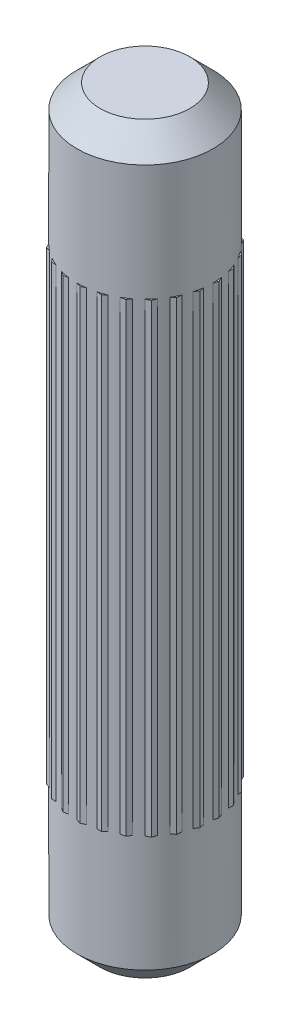
SolidWorks part; units mm, degrees
ref_plane "Front Plane" through (0, 0, 0) normal (0, 0, 1) x (1, 0, 0)
ref_plane "Top Plane" through (0, 0, 0) normal (0, 1, 0) x (1, 0, 0)
ref_plane "Right Plane" through (0, 0, 0) normal (1, 0, 0) x (0, 0, -1)
sketch "Sketch1" plane through (0, 0, 0) normal (0, 1, 0) x (1, 0, 0)
  circle A0 centre (0, 0) radius 1.465
  dimension "D1" = 2.93
extrude "Extrude1" add sketch "Sketch1" along normal mid plane 16
chamfer "Chamfer1" distance 0.5 angle 45 2 edges at (0, 8, 1.465) (0, -8, 1.465)
sketch "Sketch2" plane through (0, 0, 0) normal (0, 1, 0) x (1, 0, 0)
  line L0 (0, 0) -> (0, 1.571) construction
  line L1 (0, 0) -> (0.4172, 1.5569) construction
  line L2 (0.1912, 1.4525) -> (0.2926, 1.4712)
  line L3 (0.2926, 1.4712) -> (0.3792, 1.4151)
  line L4 (0.5606, 1.3535) -> (0.6634, 1.3453)
  line L5 (0.6634, 1.3453) -> (0.7325, 1.2687)
  line L6 (0.8918, 1.1623) -> (0.989, 1.1278)
  line L7 (0.989, 1.1278) -> (1.0359, 1.0359)
  line L8 (1.1623, 0.8918) -> (1.2472, 0.8334)
  line L9 (1.2472, 0.8334) -> (1.2687, 0.7325)
  line L10 (1.3535, 0.5606) -> (1.4204, 0.4822)
  line L11 (1.4204, 0.4822) -> (1.4151, 0.3792)
  line L12 (1.4525, 0.1912) -> (1.4968, 0.0981)
  line L13 (1.4968, 0.0981) -> (1.465, 0)
  line L14 (1.4525, -0.1912) -> (1.4712, -0.2926)
  line L15 (1.4712, -0.2926) -> (1.4151, -0.3792)
  line L16 (1.3535, -0.5606) -> (1.3453, -0.6634)
  line L17 (1.3453, -0.6634) -> (1.2687, -0.7325)
  line L18 (1.1623, -0.8918) -> (1.1278, -0.989)
  line L19 (1.1278, -0.989) -> (1.0359, -1.0359)
  line L20 (0.8918, -1.1623) -> (0.8334, -1.2472)
  line L21 (0.8334, -1.2472) -> (0.7325, -1.2687)
  line L22 (0.5606, -1.3535) -> (0.4822, -1.4204)
  line L23 (0.4822, -1.4204) -> (0.3792, -1.4151)
  line L24 (0.1912, -1.4525) -> (0.0981, -1.4968)
  line L25 (0.0981, -1.4968) -> (0, -1.465)
  line L26 (-0.1912, -1.4525) -> (-0.2926, -1.4712)
  line L27 (-0.2926, -1.4712) -> (-0.3792, -1.4151)
  line L28 (-0.5606, -1.3535) -> (-0.6634, -1.3453)
  line L29 (-0.6634, -1.3453) -> (-0.7325, -1.2687)
  line L30 (-0.8918, -1.1623) -> (-0.989, -1.1278)
  line L31 (-0.989, -1.1278) -> (-1.0359, -1.0359)
  line L32 (-1.1623, -0.8918) -> (-1.2472, -0.8334)
  line L33 (-1.2472, -0.8334) -> (-1.2687, -0.7325)
  line L34 (-1.3535, -0.5606) -> (-1.4204, -0.4822)
  line L35 (-1.4204, -0.4822) -> (-1.4151, -0.3792)
  line L36 (-1.4525, -0.1912) -> (-1.4968, -0.0981)
  line L37 (-1.4968, -0.0981) -> (-1.465, 0)
  line L38 (-1.4525, 0.1912) -> (-1.4712, 0.2926)
  line L39 (-1.4712, 0.2926) -> (-1.4151, 0.3792)
  line L40 (-1.3535, 0.5606) -> (-1.3453, 0.6634)
  line L41 (-1.3453, 0.6634) -> (-1.2687, 0.7325)
  line L42 (-1.1623, 0.8918) -> (-1.1278, 0.989)
  line L43 (-1.1278, 0.989) -> (-1.0359, 1.0359)
  line L44 (-0.8918, 1.1623) -> (-0.8334, 1.2472)
  line L45 (-0.8334, 1.2472) -> (-0.7325, 1.2687)
  line L46 (-0.5606, 1.3535) -> (-0.4822, 1.4204)
  line L47 (-0.4822, 1.4204) -> (-0.3792, 1.4151)
  line L48 (-0.1912, 1.4525) -> (-0.0981, 1.4968)
  line L49 (-0.0981, 1.4968) -> (0, 1.465)
  arc A0 (0, 1.465) -> (0.1912, 1.4525) centre (0, 0) cw
  circle A1 centre (0, 0) radius 1.465 construction
  arc A2 (0.3792, 1.4151) -> (0.5606, 1.3535) centre (0, 0) cw
  arc A3 (0.7325, 1.2687) -> (0.8918, 1.1623) centre (0, 0) cw
  arc A4 (1.0359, 1.0359) -> (1.1623, 0.8918) centre (0, 0) cw
  arc A5 (1.2687, 0.7325) -> (1.3535, 0.5606) centre (0, 0) cw
  arc A6 (1.4151, 0.3792) -> (1.4525, 0.1912) centre (0, 0) cw
  arc A7 (1.465, 0) -> (1.4525, -0.1912) centre (0, 0) cw
  arc A8 (1.4151, -0.3792) -> (1.3535, -0.5606) centre (0, 0) cw
  arc A9 (1.2687, -0.7325) -> (1.1623, -0.8918) centre (0, 0) cw
  arc A10 (1.0359, -1.0359) -> (0.8918, -1.1623) centre (0, 0) cw
  arc A11 (0.7325, -1.2687) -> (0.5606, -1.3535) centre (0, 0) cw
  arc A12 (0.3792, -1.4151) -> (0.1912, -1.4525) centre (0, 0) cw
  arc A13 (0, -1.465) -> (-0.1912, -1.4525) centre (0, 0) cw
  arc A14 (-0.3792, -1.4151) -> (-0.5606, -1.3535) centre (0, 0) cw
  arc A15 (-0.7325, -1.2687) -> (-0.8918, -1.1623) centre (0, 0) cw
  arc A16 (-1.0359, -1.0359) -> (-1.1623, -0.8918) centre (0, 0) cw
  arc A17 (-1.2687, -0.7325) -> (-1.3535, -0.5606) centre (0, 0) cw
  arc A18 (-1.4151, -0.3792) -> (-1.4525, -0.1912) centre (0, 0) cw
  arc A19 (-1.465, 0) -> (-1.4525, 0.1912) centre (0, 0) cw
  arc A20 (-1.4151, 0.3792) -> (-1.3535, 0.5606) centre (0, 0) cw
  arc A21 (-1.2687, 0.7325) -> (-1.1623, 0.8918) centre (0, 0) cw
  arc A22 (-1.0359, 1.0359) -> (-0.8918, 1.1623) centre (0, 0) cw
  arc A23 (-0.7325, 1.2687) -> (-0.5606, 1.3535) centre (0, 0) cw
  arc A24 (-0.3792, 1.4151) -> (-0.1912, 1.4525) centre (0, 0) cw
  dimension "D1" = 15
  dimension "D2" = 1.5
  dimension "D3" = 7.5
extrude "Extrude2" add sketch "Sketch2" along normal mid plane 10
